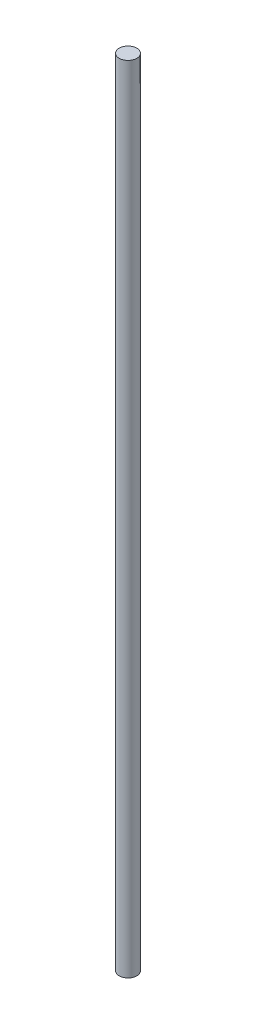
SolidWorks part; units mm, degrees
ref_plane "Front Plane" through (0, 0, 0) normal (0, 0, 1) x (1, 0, 0)
ref_plane "Top Plane" through (0, 0, 0) normal (0, 1, 0) x (1, 0, 0)
ref_plane "Right Plane" through (0, 0, 0) normal (1, 0, 0) x (0, 0, -1)
sketch "Sketch1" plane through (0, 0, 0) normal (0, 1, 0) x (1, 0, 0)
  circle A0 centre (0, 0) radius 4
  dimension "D1" = 8
extrude "Boss-Extrude1" add sketch "Sketch1" along normal blind 360
